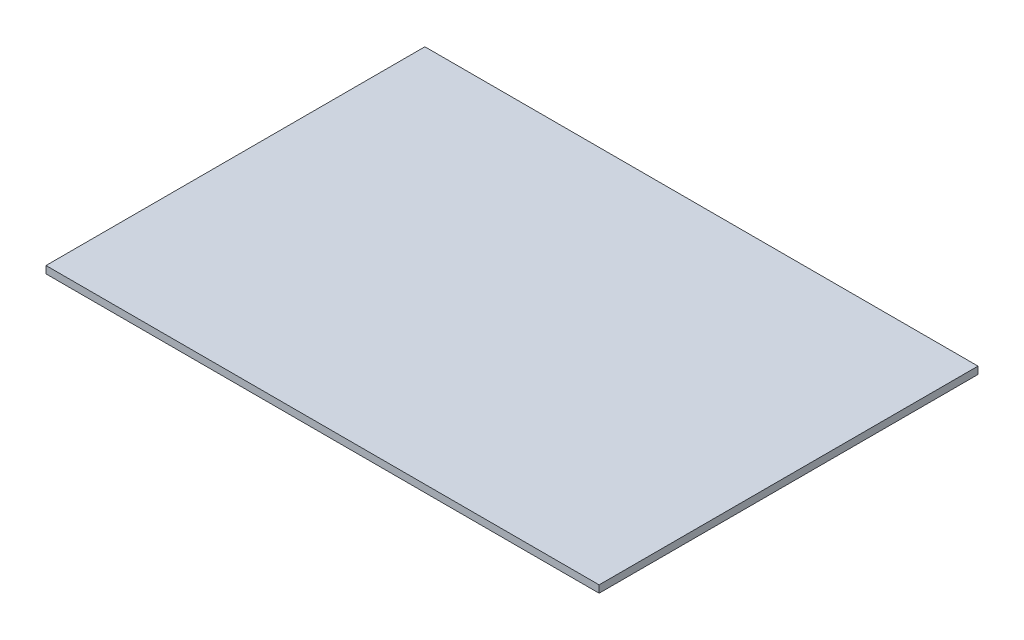
SolidWorks part; units mm, degrees
material "Beech"
ref_plane "Plan de face" through (0, 0, 0) normal (0, 0, 1) x (1, 0, 0)
ref_plane "Plan de dessus" through (0, 0, 0) normal (0, 1, 0) x (1, 0, 0)
ref_plane "Plan de droite" through (0, 0, 0) normal (1, 0, 0) x (0, 0, -1)
sketch "Sketch1" plane through (0, 0, 0) normal (0, 1, 0) x (1, 0, 0)
  line L1 (-482.6, -330.585) -> (482.6, -330.585)
  line L2 (-482.6, -330.585) -> (-482.6, 330.585)
  line L3 (-482.6, 330.585) -> (482.6, 330.585)
  line L4 (482.6, -330.585) -> (482.6, 330.585)
  line L5 (-482.6, -330.585) -> (482.6, 330.585) construction
  line L6 (-482.6, 330.585) -> (482.6, -330.585) construction
  point P0 (0, 0)
  dimension "D1" = 661.17
  dimension "D2" = 965.2
extrude "Boss-Extrude1" add sketch "Sketch1" along normal blind 12.7
